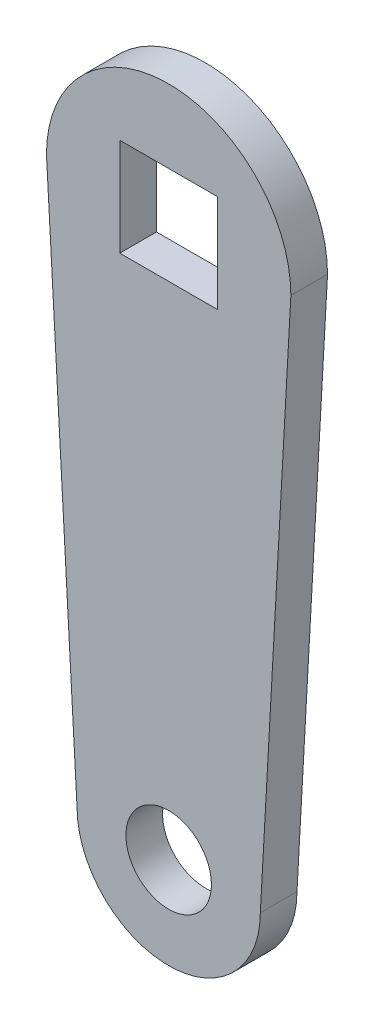
SolidWorks part; units mm, degrees
ref_plane "Alzado" through (0, 0, 0) normal (0, 0, 1) x (1, 0, 0)
ref_plane "Planta" through (0, 0, 0) normal (0, 1, 0) x (1, 0, 0)
ref_plane "Vista lateral" through (0, 0, 0) normal (1, 0, 0) x (0, 0, -1)
sketch "Croquis1" plane through (0, 0, 0) normal (0, 0, 1) x (1, 0, 0)
  line L0 (0, 0) -> (0, -3) construction
  line L1 (-10, 0) -> (-7.5, -45)
  line L2 (7.5, -45) -> (10, 0)
  line L3 (0, -10) -> (0, -45) construction
  line L5 (4, -4) -> (-4, -4)
  line L6 (4, -4) -> (4, 4)
  line L7 (4, 4) -> (-4, 4)
  line L8 (-4, -4) -> (-4, 4)
  line L9 (4, -4) -> (-4, 4) construction
  line L10 (4, 4) -> (-4, -4) construction
  arc A0 (10, 0) -> (-10, 0) centre (0, 0) ccw
  arc A1 (-7.5, -45) -> (7.5, -45) centre (0, -45) ccw
  circle A3 centre (0, -45) radius 3.5
  dimension "D1" = 20
  dimension "D2" = 15
  dimension "D3" = 7
  dimension "D4" = 8
  dimension "D5" = 8
extrude "Saliente-Extruir1" add sketch "Croquis1" along normal blind 3
